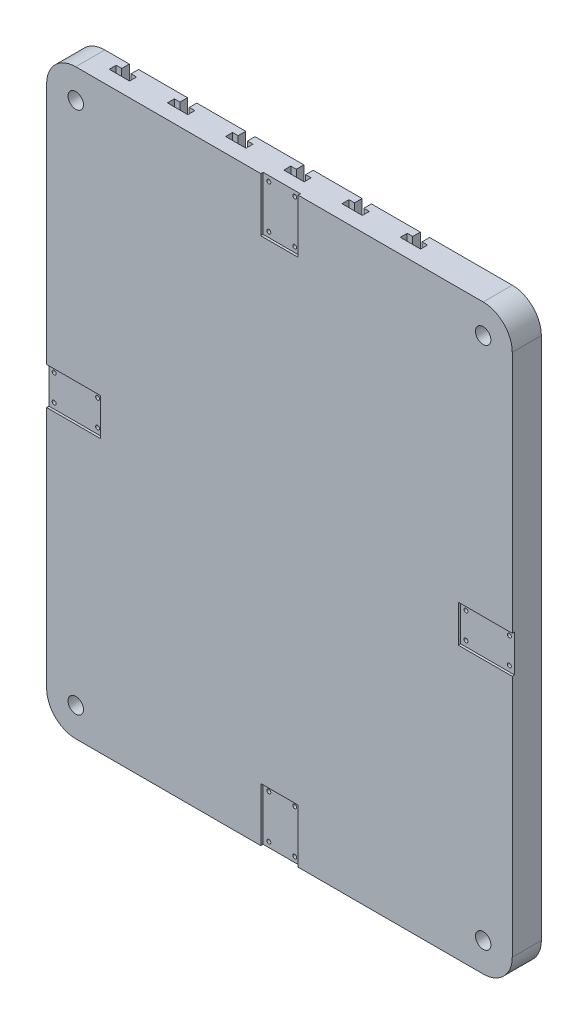
SolidWorks part; units mm, degrees
material "Q235-A"
ref_plane "前视基准面" through (0, 0, 0) normal (0, 0, 1) x (1, 0, 0)
ref_plane "上视基准面" through (0, 0, 0) normal (0, 1, 0) x (1, 0, 0)
ref_plane "右视基准面" through (0, 0, 0) normal (1, 0, 0) x (0, 0, -1)
sketch "草图1" plane through (0, 0, 0) normal (0, 0, 1) x (1, 0, 0)
  line L1 (-400, -500) -> (400, -500)
  line L2 (-400, -500) -> (-400, 500)
  line L3 (-400, 500) -> (400, 500)
  line L4 (400, -500) -> (400, 500)
  line L5 (-400, -500) -> (400, 500) construction
  line L6 (-400, 500) -> (400, -500) construction
  point P0 (0, 0)
  dimension "D1" = 800
  dimension "D2" = 1000
extrude "凸台-拉伸1" add sketch "草图1" along normal blind 50
sketch "草图3" plane through (0, 500, 0) normal (0, 1, 0) x (1, 0, 0)
  line L0 (-8, 0) -> (8, 0)
  line L1 (400, 0) -> (-400, 0) construction
  line L2 (8, 0) -> (8, -13)
  line L3 (8, -13) -> (17.5, -13)
  line L4 (17.5, -13) -> (17.5, -25)
  line L5 (17.5, -25) -> (-17.5, -25)
  line L6 (-17.5, -25) -> (-17.5, -13)
  line L7 (-17.5, -13) -> (-8, -13)
  line L8 (-8, -13) -> (-8, 0)
  line L9 (0, 0) -> (0, -25) construction
  line L11 (-400, 0) -> (400, 0) construction
  dimension "D1" = 35
  dimension "D2" = 16
  dimension "D3" = 25
  dimension "D4" = 12
  dimension "D5" = 17.5
extrude "切除-拉伸1" cut sketch "草图3" against normal through all
pattern_linear "阵列(线性)1" count 4 spacing 100 along (-1, 0, 0) count 3 spacing 100 along (1, 0, 0) of "切除-拉伸1"
fillet "圆角1" radius 50 4 edges at (400, 500, 25) (400, -500, 25) (-400, -500, 25) (-400, 500, 25)
sketch "草图5" plane through (0, 0, 50) normal (0, 0, 1) x (1, 0, 0)
  line L0 (-353.75, 0) -> (353.75, 0) construction
  line L5 (0, -453.75) -> (0, 453.75) construction
  line L12 (350, 500) -> (-350, 500) construction
  line L13 (-32, 407.5) -> (32, 407.5)
  line L19 (-32, 407.5) -> (-32, 500)
  line L20 (-32, 500) -> (32, 500)
  line L25 (32, 407.5) -> (32, 500)
  line L26 (-32, 407.5) -> (32, 500) construction
  line L27 (-400, 450) -> (-400, -450) construction
  line L32 (-32, 500) -> (32, 407.5) construction
  line L33 (-350, -500) -> (350, -500) construction
  line L34 (-307.5, -32) -> (-400, -32)
  line L35 (-307.5, -32) -> (-307.5, 32)
  line L36 (-307.5, 32) -> (-400, 32)
  line L37 (-400, -32) -> (-400, 32)
  line L38 (-307.5, -32) -> (-400, 32) construction
  line L39 (-307.5, 32) -> (-400, -32) construction
  line L40 (400, -450) -> (400, 450) construction
  line L41 (307.5, -32) -> (400, -32)
  line L42 (307.5, -32) -> (307.5, 32)
  line L43 (307.5, 32) -> (400, 32)
  line L44 (400, -32) -> (400, 32)
  line L45 (307.5, -32) -> (400, 32) construction
  line L46 (307.5, 32) -> (400, -32) construction
  line L47 (-32, -407.5) -> (32, -407.5)
  line L48 (-32, -407.5) -> (-32, -500)
  line L49 (-32, -500) -> (32, -500)
  line L50 (32, -407.5) -> (32, -500)
  line L51 (-32, -407.5) -> (32, -500) construction
  line L52 (-32, -500) -> (32, -407.5) construction
  point P0 (0, 0)
  point P4 (0, 0)
  point P9 (0, 0)
  dimension "D1" = 92.5
  dimension "D2" = 64
extrude "切除-拉伸2" cut sketch "草图5" against normal blind 4
hole_wizard "M30 螺纹孔1" positions "草图6" profile "草图7" tap size "M30" standard "GB"
sketch "草图6" plane through (0, 0, 50) normal (0, 0, 1) x (1, 0, 0)
  line L1 (-350, -450) -> (350, -450) construction
  line L2 (-350, -450) -> (-350, 450) construction
  line L3 (-350, 450) -> (350, 450) construction
  line L4 (350, -450) -> (350, 450) construction
  line L5 (-350, -450) -> (350, 450) construction
  line L6 (-350, 450) -> (350, -450) construction
  point P0 (-350, 450)
  point P4 (350, 450)
  point P6 (350, -450)
  point P10 (-350, -450)
sketch "草图7" plane through (-350, 450, 50) normal (1, 0, 0) x (0, -1, 0)
  line L0 (0, 0) -> (0, 78.4614)
  line L1 (0, 78.4614) -> (13.25, 70.5)
  line L2 (13.25, 70.5) -> (13.25, 0)
  line L5 (13.25, 0) -> (0, 0)
  line L10 (0, 78.4614) -> (-13.25, 70.5) construction
  line L11 (0, -6.35) -> (0, 107.95) construction
  dimension "螺纹孔钻头直径" = 26.5
  dimension "螺纹孔钻头深度" = 70.5
  dimension "导头角度" = 118
cosmetic thread "孔螺蚊线5" parameters "D1"=40, "D2"=30
cosmetic thread "孔螺蚊线7" parameters "D1"=40, "D2"=30
cosmetic thread "孔螺蚊线8" parameters "D1"=40, "D2"=30
cosmetic thread "孔螺蚊线10" parameters "D1"=40, "D2"=30
hole_wizard "M8 螺纹孔1" positions "草图8" profile "草图9" tap size "M8" standard "GB"
sketch "草图8" plane through (0, 0, 0) normal (0, 0, -1) x (-1, 0, 0)
  point P0 (-375, -165)
  point P2 (-375, 165)
sketch "草图9" plane through (375, -165, 0) normal (1, 0, 0) x (0, 1, 0)
  line L0 (0, 0) -> (0, 21.7929)
  line L1 (0, 21.7929) -> (3.4, 19.75)
  line L2 (3.4, 19.75) -> (3.4, 0)
  line L5 (3.4, 0) -> (0, 0)
  line L10 (0, 21.7929) -> (-3.4, 19.75) construction
  line L11 (0, -6.35) -> (0, 107.95) construction
  dimension "螺纹孔钻头直径" = 6.8
  dimension "螺纹孔钻头深度" = 19.75
  dimension "导头角度" = 118
cosmetic thread "孔螺蚊线11" parameters "D1"=16, "D2"=8
cosmetic thread "孔螺蚊线12" parameters "D1"=16, "D2"=8
hole_wizard "M8 螺纹孔2" positions "草图10" profile "草图12" tap size "M8" standard "GB"
sketch "草图10" plane through (0, 0, 46) normal (0, 0, 1) x (1, 0, 0)
  line L0 (-26.5, 416.45) -> (-18, 416.45) construction
  line L2 (18, 416.45) -> (26.5, 416.45) construction
  line L3 (18, 491.05) -> (26.5, 491.05) construction
  line L5 (-18, 491.05) -> (-26.5, 491.05) construction
  point P0 (-22.25, 416.45)
  point P2 (22.25, 416.45)
  point P4 (22.25, 491.05)
  point P6 (-22.25, 491.05)
  point P27 (25.3429, 491.0268)
  point P28 (26.3203, 491.3132)
  point P29 (18, 491.05)
  point P30 (-26.5, 491.05)
  point P31 (-22.25, 491.05)
  point P32 (21.6281, 493.0998)
  point P33 (26.5, 491.05)
  point P34 (22.25, 491.05)
sketch "草图12" plane through (-22.25, 416.45, 46) normal (1, 0, 0) x (0, -1, 0)
  line L0 (0, 0) -> (0, 19.7929)
  line L1 (0, 19.7929) -> (3.4, 17.75)
  line L2 (3.4, 17.75) -> (3.4, 0)
  line L5 (3.4, 0) -> (0, 0)
  line L10 (0, 19.7929) -> (-3.4, 17.75) construction
  line L11 (0, -6.35) -> (0, 107.95) construction
  dimension "螺纹孔钻头直径" = 6.8
  dimension "螺纹孔钻头深度" = 17.75
  dimension "导头角度" = 118
cosmetic thread "孔螺蚊线13" parameters "D1"=14, "D2"=8
cosmetic thread "孔螺蚊线14" parameters "D1"=14, "D2"=8
cosmetic thread "孔螺蚊线15" parameters "D1"=14, "D2"=8
cosmetic thread "孔螺蚊线16" parameters "D1"=14, "D2"=8
mirror "镜向1" about plane through (0, 0, 0) normal (0, 1, 0) of "M8 螺纹孔2"
hole_wizard "M8 螺纹孔3" positions "草图13" profile "草图14" tap size "M8" standard "GB"
sketch "草图13" plane through (0, 0, 46) normal (0, 0, 1) x (1, 0, 0)
  line L0 (-391.05, -26.5) -> (-391.05, -18) construction
  line L3 (-316.45, -26.5) -> (-316.45, -18) construction
  line L5 (-316.45, 18) -> (-316.45, 26.5) construction
  line L7 (-391.05, 18) -> (-391.05, 26.5) construction
  point P0 (-391.05, -22.25)
  point P2 (-391.05, 22.25)
  point P4 (-316.45, 22.25)
  point P6 (-316.45, -22.25)
  point P31 (-391.05, 22.25)
sketch "草图14" plane through (-391.05, -22.25, 46) normal (1, 0, 0) x (0, -1, 0)
  line L0 (0, 0) -> (0, 19.7929)
  line L1 (0, 19.7929) -> (3.4, 17.75)
  line L2 (3.4, 17.75) -> (3.4, 0)
  line L5 (3.4, 0) -> (0, 0)
  line L10 (0, 19.7929) -> (-3.4, 17.75) construction
  line L11 (0, -6.35) -> (0, 107.95) construction
  dimension "螺纹孔钻头直径" = 6.8
  dimension "螺纹孔钻头深度" = 17.75
  dimension "导头角度" = 118
cosmetic thread "孔螺蚊线17" parameters "D1"=14, "D2"=8
cosmetic thread "孔螺蚊线18" parameters "D1"=14, "D2"=8
cosmetic thread "孔螺蚊线19" parameters "D1"=14, "D2"=8
cosmetic thread "孔螺蚊线20" parameters "D1"=14, "D2"=8
mirror "镜向2" about plane through (0, 0, 0) normal (1, 0, 0) of "M8 螺纹孔3"
